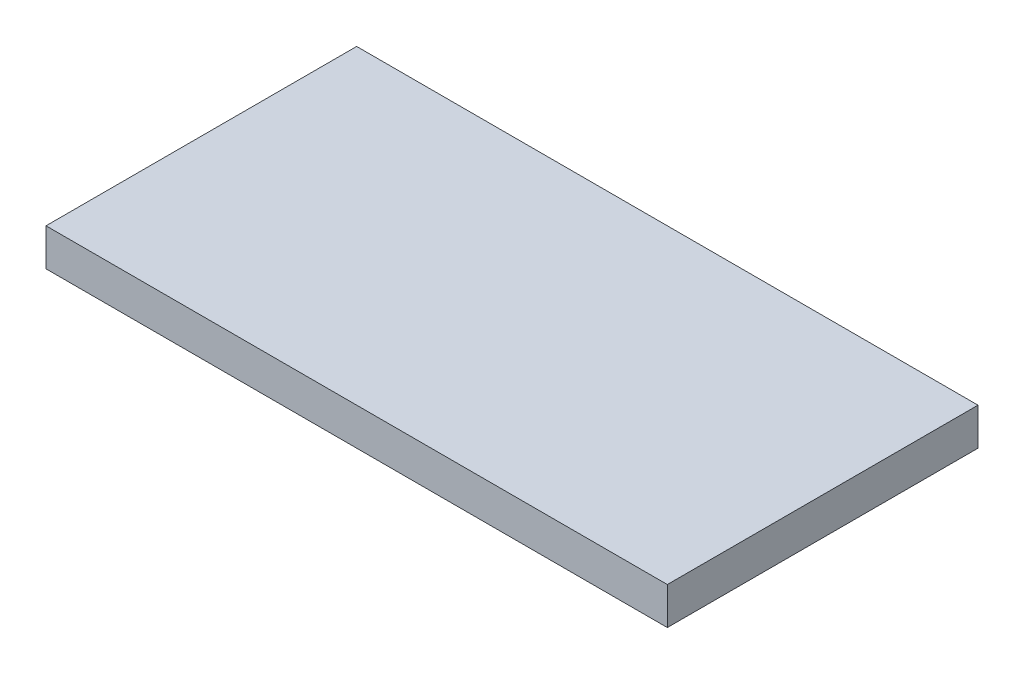
SolidWorks part; units mm, degrees
material "Pine"
ref_plane "Front Plane" through (0, 0, 0) normal (0, 0, 1) x (1, 0, 0)
ref_plane "Top Plane" through (0, 0, 0) normal (0, 1, 0) x (1, 0, 0)
ref_plane "Right Plane" through (0, 0, 0) normal (1, 0, 0) x (0, 0, -1)
sketch "Sketch1" plane through (0, 0, 0) normal (0, 1, 0) x (1, 0, 0)
  line L1 (0, 0) -> (100, 0)
  line L2 (0, 0) -> (0, 50)
  line L3 (0, 50) -> (100, 50)
  line L4 (100, 0) -> (100, 50)
  dimension "D1" = 100
  dimension "D2" = 50
extrude "Boss-Extrude1" add sketch "Sketch1" along normal blind 6
equation "\"BoardThickness\"= 6"
equation "\"D1@Boss-Extrude1\"=\"BoardThickness\""
